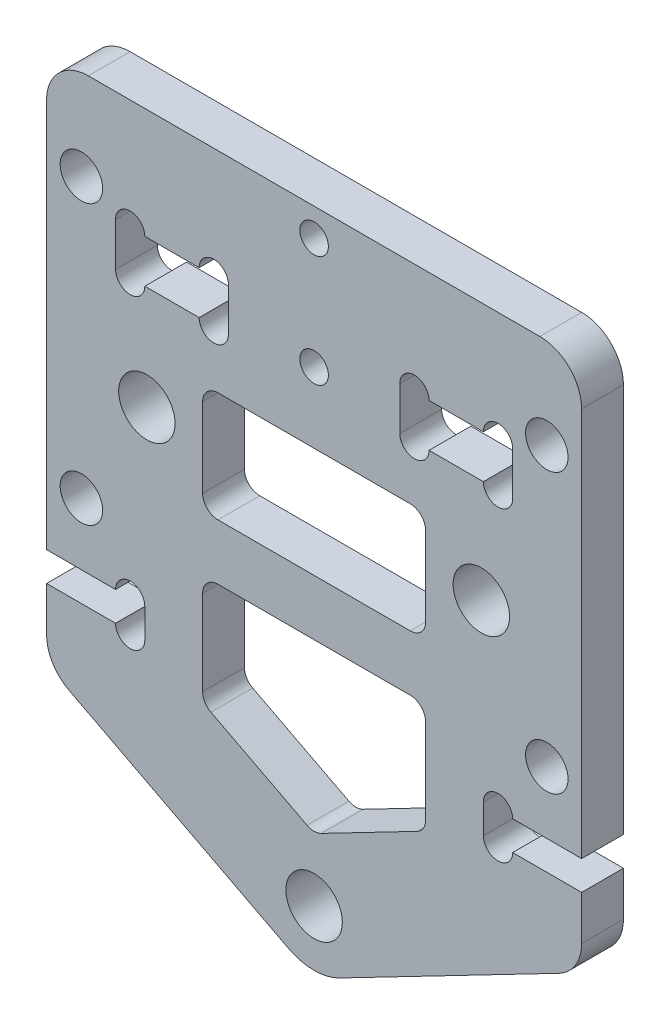
SolidWorks part; units mm, degrees
material "Thornel Mat VMA"
ref_plane "前视基准面" through (0, 0, 0) normal (0, 0, 1) x (1, 0, 0)
ref_plane "上视基准面" through (0, 0, 0) normal (0, 1, 0) x (1, 0, 0)
ref_plane "右视基准面" through (0, 0, 0) normal (1, 0, 0) x (0, 0, -1)
other "Configuration Table"
sketch "草图1" plane through (0, 0, 0) normal (0, 0, 1) x (1, 0, 0)
  line L0 (-19.2, -16.5) -> (19.2, -16.5)
  line L1 (-12, -12.5) -> (12, -12.5) construction
  line L2 (-12, -12.5) -> (-12, 12.5) construction
  line L3 (-12, 12.5) -> (12, 12.5) construction
  line L4 (12, -12.5) -> (12, 12.5) construction
  line L5 (-12, -12.5) -> (12, 12.5) construction
  line L6 (-12, 12.5) -> (12, -12.5) construction
  line L7 (19.2, -16.5) -> (19.2, 31)
  line L8 (19.2, 31) -> (-19.2, 31)
  line L9 (-19.2, 31) -> (-19.2, -16.5)
  line L10 (0, 0) -> (0, -16.5) construction
  circle A0 centre (-12, 12.5) radius 2.025
  circle A1 centre (12, 12.5) radius 2.025
  circle A2 centre (0, -12.5) radius 2.025
  point P0 (0, 0)
  dimension "D3" = 4.05
  dimension "D1" = 24
  dimension "D2" = 25
  dimension "D4" = 4
  dimension "D5" = 38.4
  dimension "D6" = 18.5
extrude "凸台-拉伸1" add sketch "草图1" along normal blind 3
sketch "草图2" plane through (0, 0, 0) normal (0, 0, -1) x (-1, 0, 0)
  circle A0 centre (0, 21) radius 0.8 construction
  circle A1 centre (0, 29) radius 0.8 construction
  circle A2 centre (0, 21) radius 0.8 construction
  circle A3 centre (0, 29) radius 0.8 construction
  circle A4 centre (0, 29) radius 1.025
  circle A5 centre (0, 21) radius 1.025
  dimension "D1" = 2.05
extrude "切除-拉伸1" cut sketch "草图2" against normal blind 43
sketch "草图3" plane through (0, 0, 3) normal (0, 0, 1) x (1, 0, 0)
  line L0 (0, 0) -> (0, -16.5) construction
  line L1 (-19.2, -16.5) -> (19.2, -16.5) construction
  line L2 (12.2, -2) -> (12.2, 0) construction
  line L3 (19.2, -2) -> (12.2, -2) construction
  line L4 (-12.2, 0) -> (-19.2, 0)
  line L5 (-19.2, 0) -> (-19.2, -2)
  line L6 (-19.2, -2) -> (-12.2, -2)
  line L7 (-12.2, -2) -> (-12.2, 0)
  line L8 (-12.2, 0) -> (-19.2, 0) construction
  line L9 (-19.2, 0) -> (-19.2, -2) construction
  line L10 (-19.2, -2) -> (-12.2, -2) construction
  line L11 (-12.2, -2) -> (-12.2, 0) construction
  line L12 (19.2, 0) -> (19.2, -2) construction
  line L13 (12.2, 0) -> (19.2, 0) construction
  line L14 (12.15, -2.05) -> (12.15, 0.05)
  line L15 (12.15, 0.05) -> (19.25, 0.05)
  line L16 (19.25, 0.05) -> (19.25, -2.05)
  line L17 (19.25, -2.05) -> (12.15, -2.05)
  line L18 (-12.15, 0.05) -> (-19.25, 0.05)
  line L19 (-19.25, 0.05) -> (-19.25, -2.05)
  line L20 (-19.25, -2.05) -> (-12.15, -2.05)
  line L21 (-12.15, -2.05) -> (-12.15, 0.05)
  dimension "D1" = 0
  dimension "D2" = 0.05
  dimension "D3" = 0.05
extrude "切除-拉伸2" cut sketch "草图3" against normal up to surface (3 mm away) up to face at (-1.025, 29, 0)
sketch "草图4" plane through (0, 0, 3) normal (0, 0, 1) x (1, 0, 0)
  line L0 (19.2, 0.05) -> (12.15, 0.05) construction
  line L1 (12.15, -2.05) -> (19.2, -2.05) construction
  line L2 (-12.15, 0.05) -> (-19.2, 0.05) construction
  line L3 (-19.2, -2.05) -> (-12.15, -2.05) construction
  circle A0 centre (13.2, 0.05) radius 1.05
  circle A1 centre (13.2, -2.05) radius 1.05
  circle A2 centre (-13.2, 0.05) radius 1.05
  circle A3 centre (-13.2, -2.05) radius 1.05
  line M1 (19.2, -2.05) -> (12.15, -2.05)
  line M3 (12.15, 0.05) -> (19.2, 0.05)
  line M7 (-19.2, 0.05) -> (-12.15, 0.05)
  line M9 (-12.15, -2.05) -> (-19.2, -2.05)
  dimension "D1" = 2.1
extrude "切除-拉伸3" cut sketch "草图4" against normal up to surface (3 mm away) contours A3 M9 | A2 M7 | A1 M1 | A0 M3 up to face at (-1.025, 29, 0)
sketch "草图5" plane through (0, 0, 0) normal (0, 0, -1) x (-1, 0, 0)
  circle A0 centre (16.7, 4.5) radius 1.525 construction
  circle A1 centre (16.7, 24.5) radius 1.525 construction
  circle A2 centre (-16.7, 24.5) radius 1.525 construction
  circle A3 centre (-16.7, 4.5) radius 1.525 construction
  circle A4 centre (16.7, 4.5) radius 1.525
  circle A5 centre (16.7, 24.5) radius 1.525
  circle A6 centre (-16.7, 24.5) radius 1.525
  circle A7 centre (-16.7, 4.5) radius 1.525
extrude "切除-拉伸4" cut sketch "草图5" against normal up to surface (3 mm away) up to face at (0, 1.0625, 3)
sketch "草图6" plane through (0, 0, 3) normal (0, 0, 1) x (1, 0, 0)
  line L0 (-6.15, 23.05) -> (-14.25, 23.05)
  line L1 (-14.25, 23.05) -> (-14.25, 19.95)
  line L2 (-14.25, 19.95) -> (-6.15, 19.95)
  line L3 (-6.15, 19.95) -> (-6.15, 23.05)
  line L4 (-6.2, 23) -> (-14.2, 23)
  line L5 (-14.2, 23) -> (-14.2, 20)
  line L6 (-14.2, 20) -> (-6.2, 20)
  line L7 (-6.2, 20) -> (-6.2, 23)
  line L8 (-6.2, 23) -> (-14.2, 23) construction
  line L9 (-14.2, 23) -> (-14.2, 20) construction
  line L10 (-14.2, 20) -> (-6.2, 20) construction
  line L11 (-6.2, 20) -> (-6.2, 23) construction
  dimension "D1" = 0
  dimension "D2" = 0.05
extrude "切除-拉伸5" cut sketch "草图6" against normal up to surface (3 mm away) up to face at (15.175, 4.5, 0)
sketch "草图7" plane through (0, 0, 3) normal (0, 0, 1) x (1, 0, 0)
  line L0 (-14.25, 19.95) -> (-6.15, 19.95) construction
  line L1 (-6.15, 23.05) -> (-14.25, 23.05) construction
  circle A0 centre (-13.2, 19.95) radius 1.05
  circle A1 centre (-13.2, 23.05) radius 1.05
  circle A2 centre (-7.2, 23.05) radius 1.05
  circle A3 centre (-7.2, 19.95) radius 1.05
  dimension "D1" = 2.1
extrude "切除-拉伸6" cut sketch "草图7" against normal up to surface (3 mm away) up to face at (-10.2, 21.5, 0)
mirror "镜向1" about plane through (0, 0, 0) normal (1, 0, 0) of "切除-拉伸6", "切除-拉伸5"
sketch "草图8" plane through (0, 0, 3) normal (0, 0, 1) x (1, 0, 0)
  line L0 (-19.2, -16.5) -> (19.2, -16.5) construction
  line L1 (1.8413, -16.051) -> (19.2, -7.05)
  line L2 (19.2, -16.5) -> (19.2, -2.05) construction
  line L3 (14.25, -2.05) -> (19.2, -2.05) construction
  line L4 (0, 0) -> (0, -12.5) construction
  line L5 (-1.8413, -16.051) -> (-19.2, -7.05)
  line L6 (-19.2, -7.05) -> (-19.2, -16.5)
  line L7 (-19.2, -16.5) -> (0, -16.5)
  line L8 (0, -16.5) -> (19.2, -16.5)
  line L9 (19.2, -16.5) -> (19.2, -7.05)
  circle A0 centre (0, -12.5) radius 4
  line M19 (-19.2, -2.05) -> (-19.2, -16.5)
  line M20 (-19.2, -16.5) -> (19.2, -16.5)
  line M21 (19.2, -16.5) -> (19.2, -2.05)
  dimension "D1" = 5
extrude "切除-拉伸7" cut sketch "草图8" against normal up to surface (3 mm away) contours A0 L5 M19 M20 | A0 L1 M20 M21 up to face at (10.2, 21.5, 0)
fillet "圆角1" radius 3 4 edges at (-19.2, -7.05, 1.5) (19.2, -7.05, 1.5) (19.2, 31, 1.5) (-19.2, 31, 1.5)
sketch "草图9" plane through (0, 0, 0) normal (0, 0, -1) x (-1, 0, 0)
  line L0 (-8, 15.95) -> (-8, -3.846)
  line L1 (-8, -3.846) -> (0, -7.9942)
  line L2 (0, -7.9942) -> (8, -3.846)
  line L3 (8, -3.846) -> (8, 15.95)
  line L4 (8, 15.95) -> (-8, 15.95)
  line L5 (0, 0) -> (0, -7.9942) construction
  line L6 (17.581, -7.8895) -> (1.8413, -16.051) construction
  line L7 (8.25, 19.95) -> (12.15, 19.95) construction
  line L8 (-17.581, -7.8895) -> (-1.8413, -16.051) construction
  line L9 (-8, 6.052) -> (8, 6.052) construction
  line L10 (-8, 4.052) -> (8, 4.052)
  line L11 (-8, 8.052) -> (8, 8.052)
  circle A0 centre (-12, 12.5) radius 2.025 construction
  dimension "D1" = 4
  dimension "D2" = 4
  dimension "D3" = 8
  dimension "D4" = 2
  dimension "D5" = 2
extrude "切除-拉伸8" cut sketch "草图9" against normal up to surface (3 mm away) contours L10 L0 L1 L2 L3 | L0 L11 L3 L4 up to face at (-10.2, 21.5, 3)
fillet "圆角2" radius 1.1 9 edges at (8, 8.052, 1.5) (8, 15.95, 1.5) (-8, 8.052, 1.5) (-8, 15.95, 1.5) (8, 4.052, 1.5) (8, -3.846, 1.5) (-8, 4.052, 1.5) (0, -7.9942, 1.5) (-8, -3.846, 1.5)
